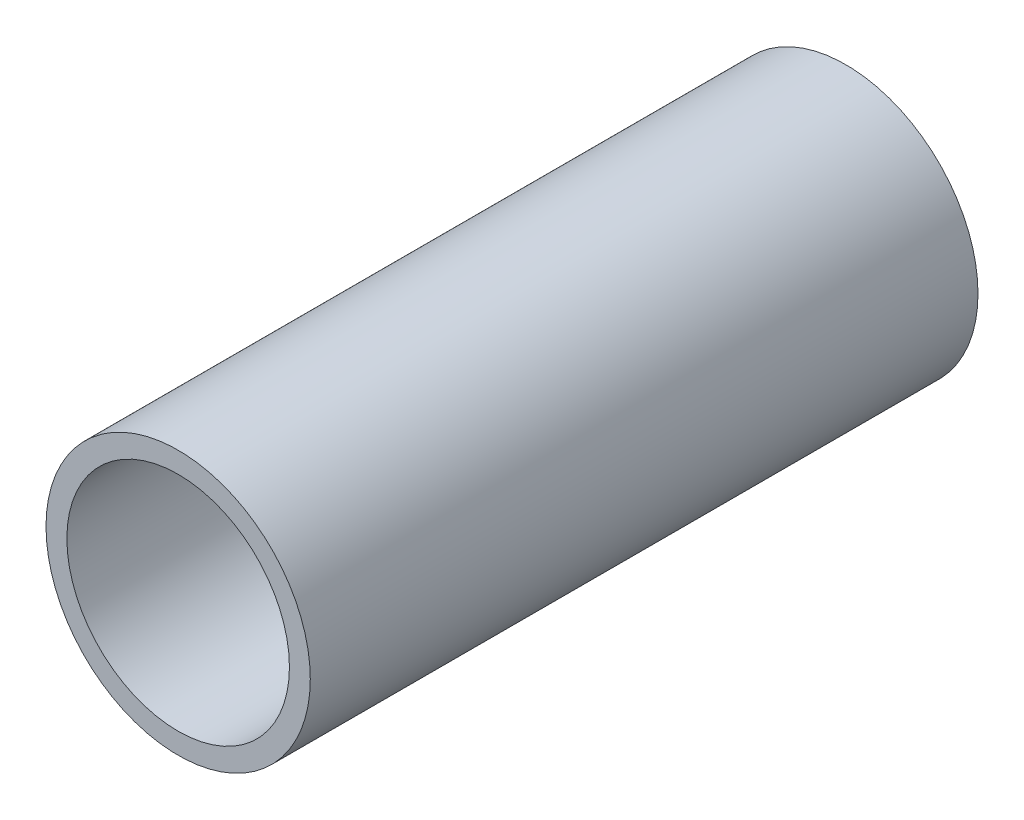
SolidWorks part; units mm, degrees
ref_plane "Front" through (0, 0, 0) normal (0, 0, 1) x (1, 0, 0)
ref_plane "Top" through (0, 0, 0) normal (0, 1, 0) x (1, 0, 0)
ref_plane "Right" through (0, 0, 0) normal (1, 0, 0) x (0, 0, -1)
sketch "Sketch2" plane through (0, 0, 0) normal (0, 0, 1) x (1, 0, 0)
  circle A0 centre (0, 0) radius 26.6665
  circle A1 centre (0, 0) radius 31.6665
  dimension "D2" = 53.333
  dimension "D1" = 5
extrude "Boss-Extrude1" add sketch "Sketch2" along normal blind 160
